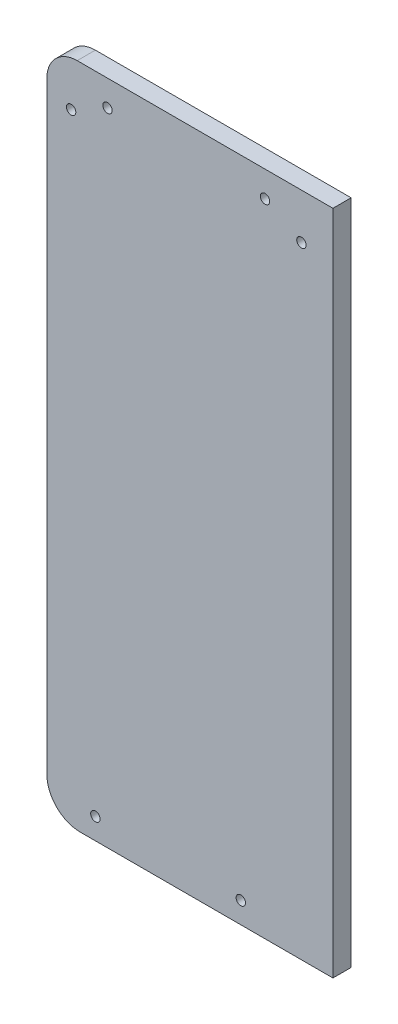
SolidWorks part; units mm, degrees
ref_plane "Płaszczyzna przednia" through (0, 0, 0) normal (0, 0, 1) x (1, 0, 0)
ref_plane "Płaszczyzna górna" through (0, 0, 0) normal (0, 1, 0) x (1, 0, 0)
ref_plane "Płaszczyzna prawa" through (0, 0, 0) normal (1, 0, 0) x (0, 0, -1)
sketch "Szkic2" plane through (0, 0, 0) normal (0, 0, 1) x (1, 0, 0)
  line L0 (-10.1, -383.604) -> (-94, -383.604) construction
  line L4 (-10.6, -166.604) -> (-10.6, -386.604)
  line L8 (-10.6, -386.604) -> (-94, -386.604)
  line L11 (-105, -375.604) -> (-105, -176.604)
  line L12 (-95, -166.604) -> (-10.6, -166.604)
  arc A0 (-95, -166.604) -> (-105, -176.604) centre (-95, -176.604) ccw
  arc A4 (-105, -375.604) -> (-94, -386.604) centre (-94, -375.604) ccw
  point P7 (-9.1, -168.604)
  point P9 (-9.1, -384.604)
  point P18 (-94, -166.604)
  dimension "D3" = 10
  dimension "D1" = 220
  dimension "D2" = 3
extrude "Dodanie-wyciągnięcie1" add sketch "Szkic2" along normal blind 6
sketch "Szkic4" plane through (0, 0, 6) normal (0, 0, 1) x (1, 0, 0)
  circle A0 centre (-41, -379.604) radius 1.55 construction
  circle A1 centre (-89, -379.604) radius 1.55 construction
  circle A2 centre (-41, -379.604) radius 1.55
  circle A3 centre (-89, -379.604) radius 1.55
extrude "Wytnij-wyciągnięcie1" cut sketch "Szkic4" against normal blind 6
sketch "Szkic7" plane through (0, 0, 6) normal (0, 0, 1) x (1, 0, 0)
  circle A0 centre (-21, -181.604) radius 1.55 construction
  circle A1 centre (-21, -181.604) radius 1.55
  circle A2 centre (-97, -181.604) radius 1.55 construction
  circle A3 centre (-97, -181.604) radius 1.55
  circle A4 centre (-85, -175.104) radius 1.55 construction
  circle A5 centre (-33, -175.104) radius 1.55 construction
  circle A6 centre (-85, -175.104) radius 1.55
  circle A7 centre (-33, -175.104) radius 1.55
extrude "Wytnij-wyciągnięcie3" cut sketch "Szkic7" against normal blind 6
